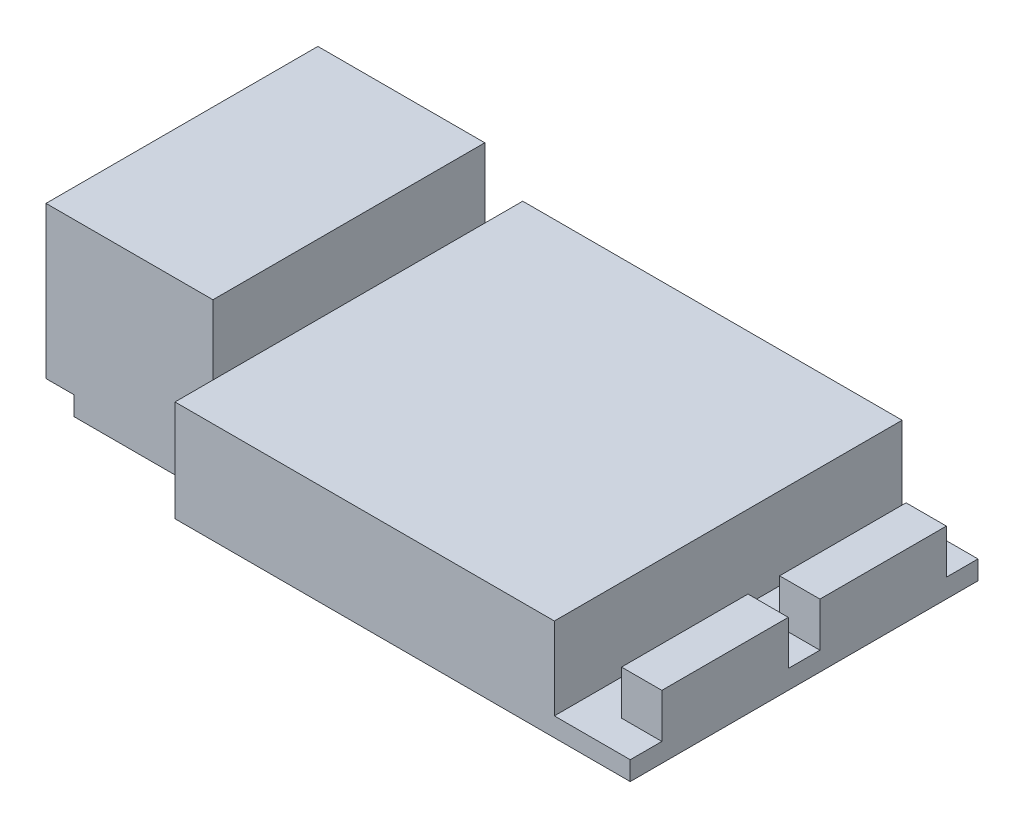
SolidWorks part; units mm, degrees
ref_plane "前视基准面" through (0, 0, 0) normal (0, 0, 1) x (1, 0, 0)
ref_plane "上视基准面" through (0, 0, 0) normal (0, 1, 0) x (1, 0, 0)
ref_plane "右视基准面" through (0, 0, 0) normal (1, 0, 0) x (0, 0, -1)
other "Configuration Table"
sketch "草图1" plane through (0, 0, 0) normal (0, 1, 0) x (1, 0, 0)
  line L0 (-23.5, 10.75) -> (-12.5, 10.75)
  line L1 (-12.5, -13.75) -> (23.5, -13.75)
  line L2 (-23.5, -10.75) -> (-23.5, 10.75)
  line L3 (-12.5, 13.75) -> (23.5, 13.75)
  line L4 (23.5, -13.75) -> (23.5, 13.75)
  line L7 (-12.5, 10.75) -> (-12.5, 13.75)
  line L8 (0, 0) -> (-23.5, 0) construction
  line L9 (-23.5, -10.75) -> (-12.5, -10.75)
  line L10 (-12.5, -10.75) -> (-12.5, -13.75)
  point P0 (0, 0)
  dimension "D2" = 27.5
  dimension "D3" = 11
  dimension "D4" = 21.5
extrude "凸台-拉伸1" add sketch "草图1" along normal blind 1.5 contours L3 L4 L1 L10 L9 L2 L0 L7
sketch "草图2" plane through (0, 1.5, 0) normal (0, 1, 0) x (1, 0, 0)
  line L0 (-12.5, -13.75) -> (23.5, -13.75) construction
  line L1 (-12.5, 13.75) -> (17.5, 13.75)
  line L2 (-12.5, 13.75) -> (-12.5, -13.75)
  line L3 (-12.5, -13.75) -> (17.5, -13.75)
  line L4 (17.5, 13.75) -> (17.5, -13.75)
  dimension "D1" = 30
extrude "凸台-拉伸2" add sketch "草图2" along normal blind 6.5
sketch "草图3" plane through (0, 1.5, 0) normal (0, 1, 0) x (1, 0, 0)
  line L0 (-23.5, -10.75) -> (-12.5, -10.75) construction
  line L1 (-12.5, 10.75) -> (-25.7, 10.75)
  line L2 (-12.5, 10.75) -> (-12.5, -10.75)
  line L3 (-12.5, -10.75) -> (-25.7, -10.75)
  line L4 (-25.7, 10.75) -> (-25.7, -10.75)
  dimension "D1" = 13.2
extrude "凸台-拉伸3" add sketch "草图3" along normal blind 12
sketch "草图4" plane through (0, 1.5, 0) normal (0, 1, 0) x (1, 0, 0)
  line L0 (0, 0) -> (23.5, 0) construction
  line L1 (20.3115, 11.25) -> (23.5, 11.25)
  line L2 (20.3115, 11.25) -> (20.3115, 1.25)
  line L3 (20.3115, 1.25) -> (23.5, 1.25)
  line L4 (23.5, 11.25) -> (23.5, 1.25)
  line L5 (23.5, -13.75) -> (23.5, 13.75) construction
  line L6 (17.5, 13.75) -> (23.5, 13.75) construction
  line L7 (20.3115, -1.25) -> (23.5, -1.25)
  line L8 (23.5, -11.25) -> (23.5, -1.25)
  line L9 (20.3115, -11.25) -> (23.5, -11.25)
  line L10 (20.3115, -11.25) -> (20.3115, -1.25)
  dimension "D1" = 10
  dimension "D2" = 2.5
extrude "凸台-拉伸4" add sketch "草图4" along normal blind 3.5
